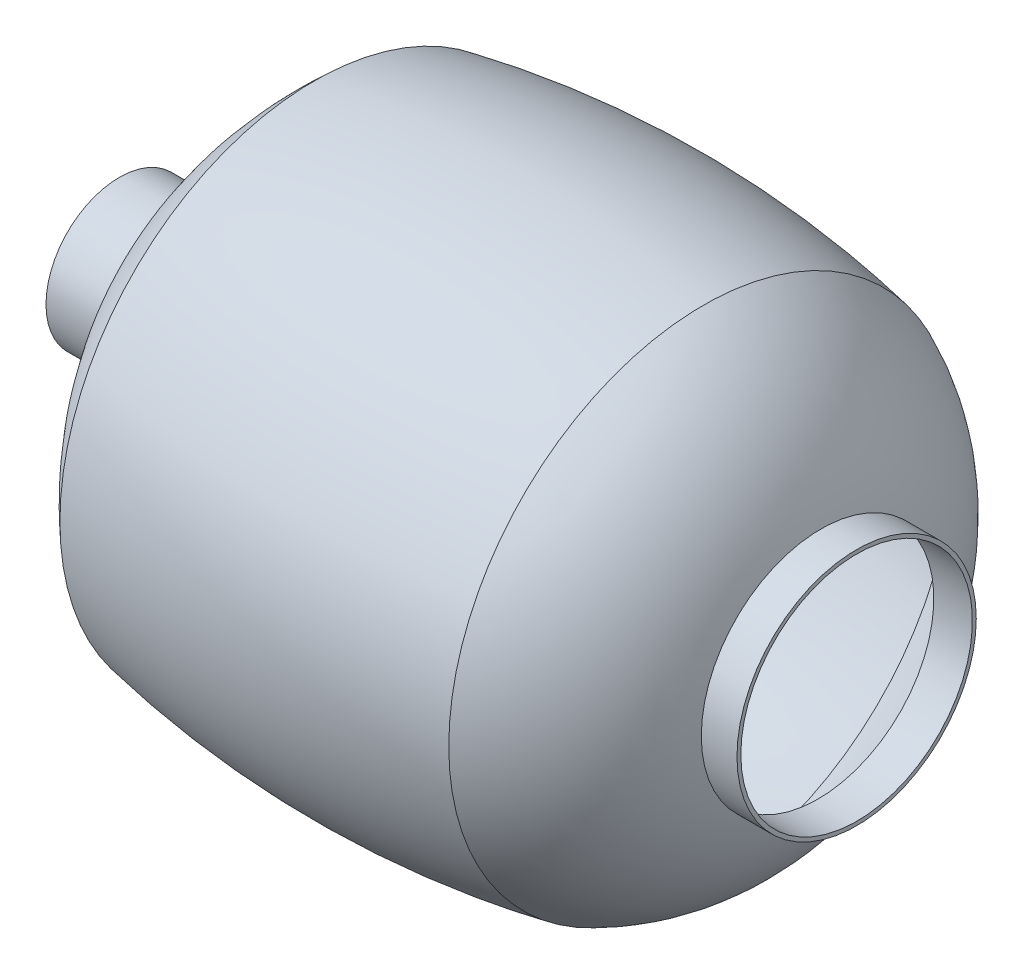
SolidWorks part; units mm, degrees
ref_plane "Front Plane" through (0, 0, 0) normal (0, 0, 1) x (1, 0, 0)
ref_plane "Top Plane" through (0, 0, 0) normal (0, 1, 0) x (1, 0, 0)
ref_plane "Right Plane" through (0, 0, 0) normal (1, 0, 0) x (0, 0, -1)
sketch "Sketch1" plane through (0, 0, 0) normal (0, 0, 1) x (1, 0, 0)
  line L0 (90, -30) -> (90, -31)
  line L1 (80.761, -31) -> (91, -31) construction
  line L2 (-101, 0) -> (90, 0) construction
  line L3 (0, 0) -> (0, -65) construction
  line L4 (-80, -18) -> (-101, -18)
  line L5 (0, -65) -> (-50, -65) construction
  line L6 (90, -30) -> (80, -30)
  line L11 (-80, 0) -> (80, 0) construction
  line L17 (80.761, -31) -> (90, -31)
  line L18 (-80.7333, -19) -> (-101, -19)
  line L19 (-101, -19) -> (-101, -18)
  line L22 (-101, -19) -> (-101, 1) construction
  line L23 (-100, -18) -> (-100, 0) construction
  line L24 (-101, 1) -> (-80, 1) construction
  line L25 (-100, 0) -> (-80, 0) construction
  line L26 (-80, 1) -> (79.5935, 1) construction
  line L27 (90, -30) -> (90, 0.0359) construction
  line L28 (91, -31) -> (91, 1.0359) construction
  line L29 (91, 1.0359) -> (79.6304, 1.0359) construction
  line L30 (90, 0.0359) -> (80.0369, 0.0359) construction
  line L31 (79.5935, 1) -> (79.6304, 1.0359) construction
  line L32 (80, 0) -> (80.0369, 0.0359) construction
  line L33 (-80, -18) -> (-100, -18) construction
  line L34 (80, -30) -> (90, -30) construction
  arc A0 (-50, -65) -> (-80, -18) centre (21.1614, 13.4967) cw
  arc A1 (50, -65) -> (80, -30) centre (28.3897, -16.1197) ccw
  arc A2 (50, -65) -> (-50, -65) centre (0, 196.3165) cw
  arc A3 (50.2996, -65.9608) -> (80.761, -31) centre (28.3897, -16.1197) ccw
  arc A4 (50.2996, -65.9608) -> (-50.4632, -65.9294) centre (0, 196.3165) cw
  arc A5 (-50.4632, -65.9294) -> (-80.7333, -19) centre (21.1614, 13.4967) cw
  dimension "D2" = 65
  dimension "D4" = 160
  dimension "D5" = 191
  dimension "D6" = 100
  dimension "D7" = 10
revolve "Revolve12" add sketch "Sketch1" angle 360 about L2
